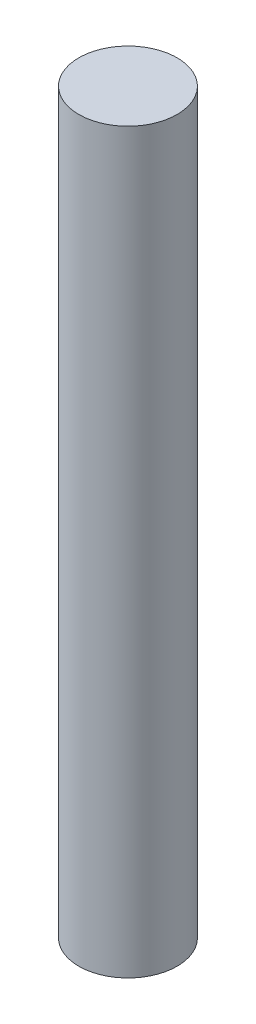
SolidWorks part; units mm, degrees
ref_plane "Front Plane" through (0, 0, 0) normal (0, 0, 1) x (1, 0, 0)
ref_plane "Top Plane" through (0, 0, 0) normal (0, 1, 0) x (1, 0, 0)
ref_plane "Right Plane" through (0, 0, 0) normal (1, 0, 0) x (0, 0, -1)
sketch "Sketch1" plane through (0, 0, 0) normal (0, 1, 0) x (1, 0, 0)
  circle A0 centre (0, 0) radius 5
  point P3 (-24.0975, 24.2074)
  dimension "D1" = 10
extrude "Boss-Extrude1" add sketch "Sketch1" along normal blind 65.0556 and the other way blind 10 contours A0
